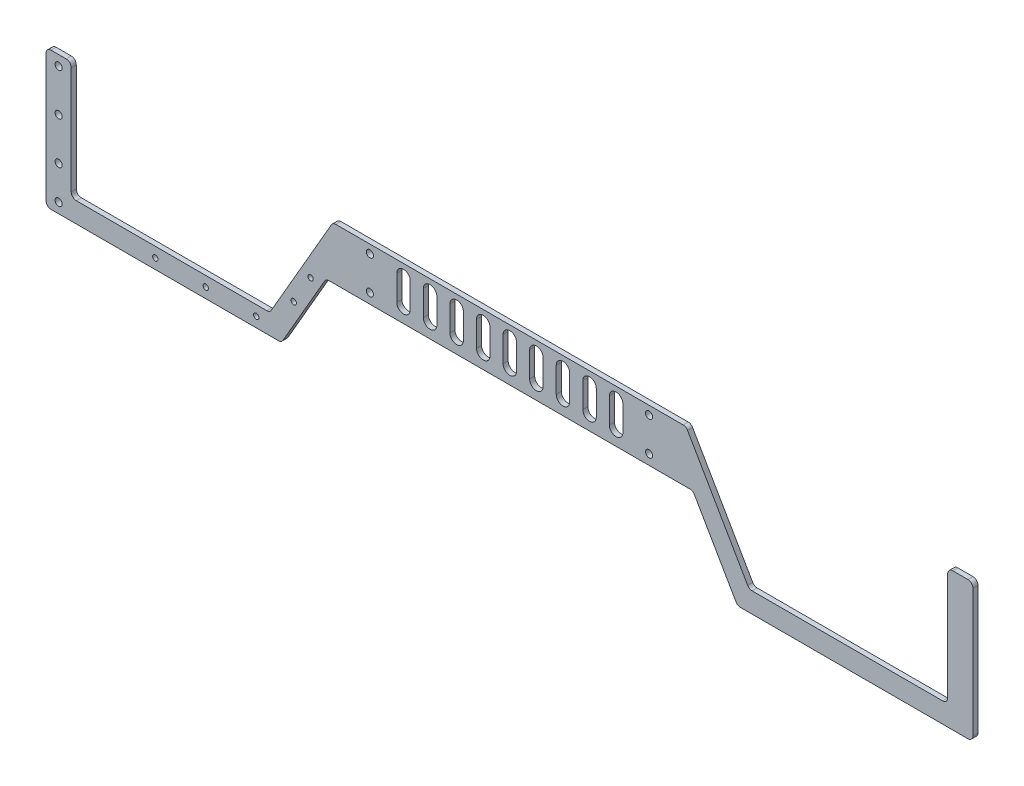
SolidWorks part; units mm, degrees
material "Thornel Mat VMA"
ref_plane "前视基准面" through (0, 0, 0) normal (0, 0, 1) x (1, 0, 0)
ref_plane "上视基准面" through (0, 0, 0) normal (0, 1, 0) x (1, 0, 0)
ref_plane "右视基准面" through (0, 0, 0) normal (1, 0, 0) x (0, 0, -1)
other "Configuration Table"
sketch "草图1" plane through (0, 0, 0) normal (0, 0, 1) x (1, 0, 0)
  line L0 (20.1923, -5) -> (109.0415, -5)
  line L1 (20.1923, -5) -> (-20.1923, -5)
  line L3 (105, 26) -> (-105, 26)
  line L5 (20.1923, -5) -> (-105, 26) construction
  line L6 (105, 26) -> (-20.1923, -5) construction
  line L7 (109.0415, -5) -> (135.5718, -50.9519)
  line L8 (135.5718, -50.9519) -> (275.5718, -50.9519)
  line L9 (275.5718, -50.9519) -> (275.5718, 31.0481)
  line L10 (275.5718, 31.0481) -> (260.5718, 31.0481)
  line L11 (260.5718, 31.0481) -> (260.5718, -38.9519)
  line L12 (260.5718, -38.9519) -> (142.5, -38.9519)
  line L13 (142.5, -38.9519) -> (105, 26)
  line L15 (0, 26) -> (0, -5) construction
  line L17 (-142.5, -38.9519) -> (-105, 26)
  line L18 (-260.5718, -38.9519) -> (-142.5, -38.9519)
  line L19 (-260.5718, 31.0481) -> (-260.5718, -38.9519)
  line L20 (-275.5718, 31.0481) -> (-260.5718, 31.0481)
  line L21 (-275.5718, -50.9519) -> (-275.5718, 31.0481)
  line L22 (-135.5718, -50.9519) -> (-275.5718, -50.9519)
  line L23 (-109.0415, -5) -> (-135.5718, -50.9519)
  line L24 (-20.1923, -5) -> (-109.0415, -5)
  line L25 (-268.0718, 31.0481) -> (-268.0718, -44.9519) construction
  line L26 (-268.0718, -44.9519) -> (-139.0359, -44.9519) construction
  line L27 (-139.0359, -44.9519) -> (-105.1929, 13.6658) construction
  circle A0 centre (-118.2791, -9) radius 1.6
  circle A1 centre (-128.2791, -26.3205) radius 1.6
  circle A2 centre (-150.5718, -44.9519) radius 1.6
  circle A3 centre (-180.5718, -44.9519) radius 1.6
  circle A4 centre (-210.5718, -44.9519) radius 1.6
  circle A5 centre (-268.0718, -44.9519) radius 2.1
  circle A6 centre (-268.0718, -24.9519) radius 2.1
  circle A7 centre (-268.0718, 0.0481) radius 2.1
  circle A8 centre (-268.0718, 25.0481) radius 2.1
  point P0 (0, 0)
  dimension "D13" = 3.2
  dimension "D14" = 4.2
  dimension "D15" = 20
  dimension "D16" = 25
  dimension "D17" = 25
  dimension "D18" = 20
  dimension "D19" = 35
  dimension "D20" = 30
  dimension "D21" = 30
  dimension "D22" = 125
  dimension "D1" = 15
  dimension "D2" = 12
  dimension "D3" = 12
  dimension "D4" = 210
  dimension "D5" = 31
  dimension "D6" = 75
  dimension "D7" = 120
  dimension "D8" = 5
  dimension "D9" = 140
  dimension "D10" = 70
  dimension "D11" = 6
  dimension "D12" = 6
extrude "凸台-拉伸2" add sketch "草图1" along normal blind 3
sketch "草图2" plane through (0, 0, 3) normal (0, 0, 1) x (1, 0, 0)
  line L0 (0, 24.7885) -> (0, -5) construction
  line L2 (-109.0415, -5) -> (109.0415, -5) construction
  line L3 (-83, 24.7885) -> (-83, -5) construction
  line L4 (83, 24.7885) -> (83, -5) construction
  line L5 (105, 26) -> (-105, 26) construction
  circle A0 centre (-83, 21) radius 2.1
  circle A1 centre (-83, 1) radius 2.1
  circle A2 centre (83, 1) radius 2.1
  circle A3 centre (83, 21) radius 2.1
  dimension "D1" = 4.2
  dimension "D2" = 20
  dimension "D4" = 5
  dimension "D3" = 83
extrude "切除-拉伸1" cut sketch "草图2" against normal blind 3
fillet "圆角1" radius 3
sketch "草图3" plane through (0, 0, 3) normal (0, 0, 1) x (1, 0, 0)
  line L0 (-63, 19) -> (-63, 4) construction
  line L1 (-59, 19) -> (-59, 4)
  line L2 (-67, 19) -> (-67, 4)
  line L3 (103.2679, 26) -> (-103.2679, 26) construction
  line L4 (-51.2, 19) -> (-51.2, 4)
  line L5 (-43.2, 19) -> (-43.2, 4)
  line L6 (-47.2, 19) -> (-47.2, 4) construction
  line L7 (-35.4, 19) -> (-35.4, 4)
  line L8 (-27.4, 19) -> (-27.4, 4)
  line L9 (-31.4, 19) -> (-31.4, 4) construction
  line L10 (-19.6, 19) -> (-19.6, 4)
  line L11 (-11.6, 19) -> (-11.6, 4)
  line L12 (-15.6, 19) -> (-15.6, 4) construction
  line L13 (-3.8, 19) -> (-3.8, 4)
  line L14 (4.2, 19) -> (4.2, 4)
  line L15 (0.2, 19) -> (0.2, 4) construction
  line L16 (12, 19) -> (12, 4)
  line L17 (20, 19) -> (20, 4)
  line L18 (16, 19) -> (16, 4) construction
  line L19 (27.8, 19) -> (27.8, 4)
  line L20 (35.8, 19) -> (35.8, 4)
  line L21 (31.8, 19) -> (31.8, 4) construction
  line L22 (43.6, 19) -> (43.6, 4)
  line L23 (51.6, 19) -> (51.6, 4)
  line L24 (47.6, 19) -> (47.6, 4) construction
  line L27 (67, 19) -> (67, 4) construction
  line L30 (83, 19) -> (83, 4) construction
  line L33 (99, 19) -> (99, 4) construction
  line L36 (115, 19) -> (115, 4) construction
  line L39 (131, 19) -> (131, 4) construction
  line L42 (147, 19) -> (147, 4) construction
  line L43 (59.4, 19) -> (59.4, 4)
  line L44 (67.4, 19) -> (67.4, 4)
  line L45 (63.4, 19) -> (63.4, 4) construction
  line L48 (81, 19) -> (81, 4) construction
  arc A0 (-59, 19) -> (-67, 19) centre (-63, 19) ccw
  arc A1 (-67, 4) -> (-59, 4) centre (-63, 4) ccw
  circle A2 centre (-83, 21) radius 2.1 construction
  arc A3 (-43.2, 19) -> (-51.2, 19) centre (-47.2, 19) ccw
  arc A4 (-51.2, 4) -> (-43.2, 4) centre (-47.2, 4) ccw
  arc A5 (-27.4, 19) -> (-35.4, 19) centre (-31.4, 19) ccw
  arc A6 (-35.4, 4) -> (-27.4, 4) centre (-31.4, 4) ccw
  arc A7 (-11.6, 19) -> (-19.6, 19) centre (-15.6, 19) ccw
  arc A8 (-19.6, 4) -> (-11.6, 4) centre (-15.6, 4) ccw
  arc A9 (4.2, 19) -> (-3.8, 19) centre (0.2, 19) ccw
  arc A10 (-3.8, 4) -> (4.2, 4) centre (0.2, 4) ccw
  arc A11 (20, 19) -> (12, 19) centre (16, 19) ccw
  arc A12 (12, 4) -> (20, 4) centre (16, 4) ccw
  arc A13 (35.8, 19) -> (27.8, 19) centre (31.8, 19) ccw
  arc A14 (27.8, 4) -> (35.8, 4) centre (31.8, 4) ccw
  arc A15 (51.6, 19) -> (43.6, 19) centre (47.6, 19) ccw
  arc A16 (43.6, 4) -> (51.6, 4) centre (47.6, 4) ccw
  arc A17 (67.4, 19) -> (59.4, 19) centre (63.4, 19) ccw
  arc A18 (59.4, 4) -> (67.4, 4) centre (63.4, 4) ccw
  point P2 (-63, 11.5)
  point P14 (-47.2, 11.5)
  point P21 (-31.4, 11.5)
  point P28 (-15.6, 11.5)
  point P35 (0.2, 11.5)
  point P42 (16, 11.5)
  point P49 (31.8, 11.5)
  point P56 (47.6, 11.5)
  point P63 (67, 11.5)
  point P65 (63.4, 11.5)
  point P70 (83, 11.5)
  point P77 (99, 11.5)
  point P78 (81, 11.5)
  point P84 (115, 11.5)
  point P91 (131, 11.5)
  point P98 (147, 11.5)
  dimension "D1" = 4
  dimension "D3" = 7
  dimension "D2" = 15
  dimension "D4" = 16
  dimension "D6" = 7.8
  dimension "D5" = 9
extrude "切除-拉伸2" cut sketch "草图3" against normal through all
equation "\"、\"=10"
